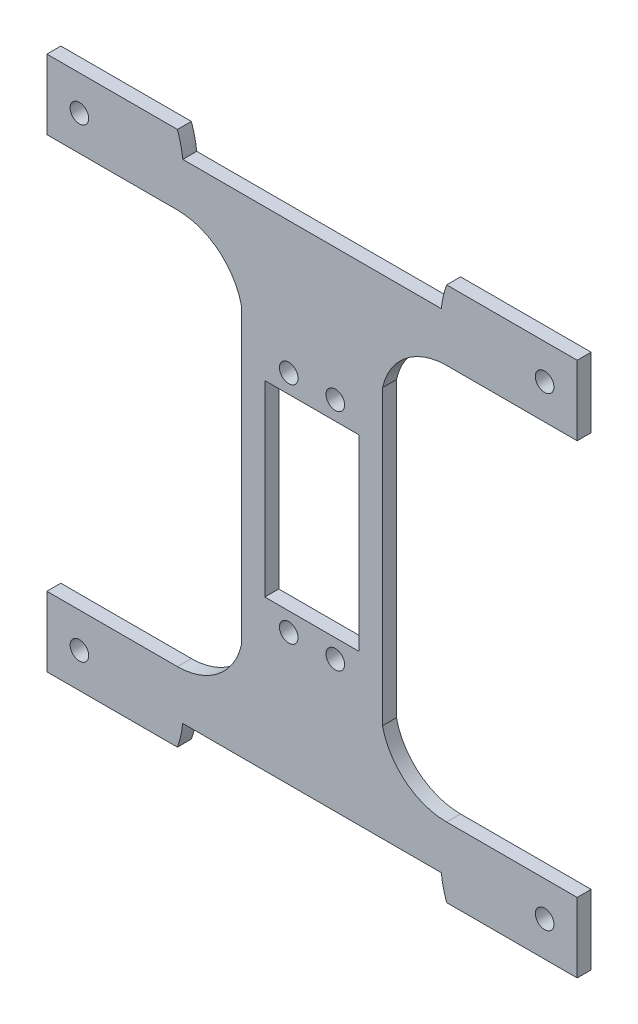
SolidWorks part; units mm, degrees
ref_plane "Alzado" through (0, 0, 0) normal (0, 0, 1) x (1, 0, 0)
ref_plane "Planta" through (0, 0, 0) normal (0, 1, 0) x (1, 0, 0)
ref_plane "Vista lateral" through (0, 0, 0) normal (1, 0, 0) x (0, 0, -1)
sketch "Croquis2" plane through (0, 0, 0) normal (0, 0, 1) x (1, 0, 0)
  line L4 (70, 90) -> (70, -10) construction
  line L5 (20, 40) -> (120, 40) construction
  line L11 (20, 90) -> (20, -10) construction
  line L24 (20, 90) -> (120, 90) construction
  line L25 (120, 90) -> (120, -10) construction
  line L26 (59.85, 60.15) -> (80.15, 60.15)
  line L27 (59.85, 60.15) -> (59.85, 19.85)
  line L28 (59.85, 19.85) -> (80.15, 19.85)
  line L29 (80.15, 60.15) -> (80.15, 19.85)
  line L30 (59.85, 60.15) -> (80.15, 19.85) construction
  line L31 (59.85, 19.85) -> (80.15, 60.15) construction
  line L41 (120, -10) -> (20, -10) construction
  line L51 (54.85, 71.478) -> (54.85, 8.522)
  line L53 (85.15, 71.478) -> (85.15, 8.522)
  line L54 (54.85, 71.478) -> (85.15, 8.522) construction
  line L55 (54.85, 8.522) -> (85.15, 71.478) construction
  line L59 (72.5, 92.5) -> (97.7795, 92.5)
  line L60 (67.5, 92.5) -> (42.2205, 92.5)
  line L61 (67.5, 92.5) -> (72.5, 92.5)
  line L66 (67.5, -12.5) -> (42.2205, -12.5)
  line L67 (67.5, -12.5) -> (72.5, -12.5)
  line L68 (72.5, -12.5) -> (97.7795, -12.5)
  line L69 (13, 82.5) -> (41.0654, 82.5)
  line L70 (13, 97.5) -> (41.0654, 97.5)
  line L71 (127, 82.5) -> (98.9346, 82.5)
  line L72 (127, 97.5) -> (98.9346, 97.5)
  line L73 (127, -17.5) -> (98.9346, -17.5)
  line L74 (127, -2.5) -> (98.9346, -2.5)
  line L75 (13, -2.5) -> (41.0654, -2.5)
  line L76 (13, -17.5) -> (41.0654, -17.5)
  line L79 (13, -2.5) -> (13, -17.5)
  line L80 (13, 82.5) -> (13, 97.5)
  line L81 (127, -2.5) -> (127, -17.5)
  line L82 (127, 82.5) -> (127, 97.5)
  circle A16 centre (65, 64.15) radius 2
  circle A17 centre (75, 64.15) radius 2
  circle A18 centre (75, 15.85) radius 2
  circle A19 centre (65, 15.85) radius 2
  circle A20 centre (20, -10) radius 2
  circle A21 centre (120, -10) radius 2
  circle A22 centre (120, 90) radius 2
  circle A23 centre (20, 90) radius 2
  arc A25 (41.0654, 97.5) -> (42.2205, 92.5) centre (20, 90) cw
  arc A26 (98.9346, -17.5) -> (97.7795, -12.5) centre (120, -10) cw
  arc A28 (41.0654, -17.5) -> (42.2205, -12.5) centre (20, -10) ccw
  arc A30 (98.9346, 97.5) -> (97.7795, 92.5) centre (120, 90) ccw
  arc A36 (41.0654, -2.5) -> (54.85, 8.522) centre (41.0654, 11.6309) ccw
  arc A37 (98.9346, -2.5) -> (85.15, 8.522) centre (98.9346, 11.6309) cw
  arc A38 (98.9346, 82.5) -> (85.15, 71.478) centre (98.9346, 68.3691) ccw
  arc A39 (41.0654, 82.5) -> (54.85, 71.478) centre (41.0654, 68.3691) cw
  point P11 (70, 40)
  point P17 (70, 40)
  point P18 (70, 40)
  dimension "D2" = 28.0654
  dimension "D5" = 20.3
  dimension "D6" = 4
  dimension "D8" = 4
  dimension "D9" = 4
  dimension "D10" = 100
  dimension "D11" = 5
  dimension "D4" = 40.3
  dimension "D7" = 10
  dimension "D14" = 10
  dimension "D16" = 7
  dimension "D17" = 15
extrude "Saliente-Extruir2" add sketch "Croquis2" along normal blind 3
